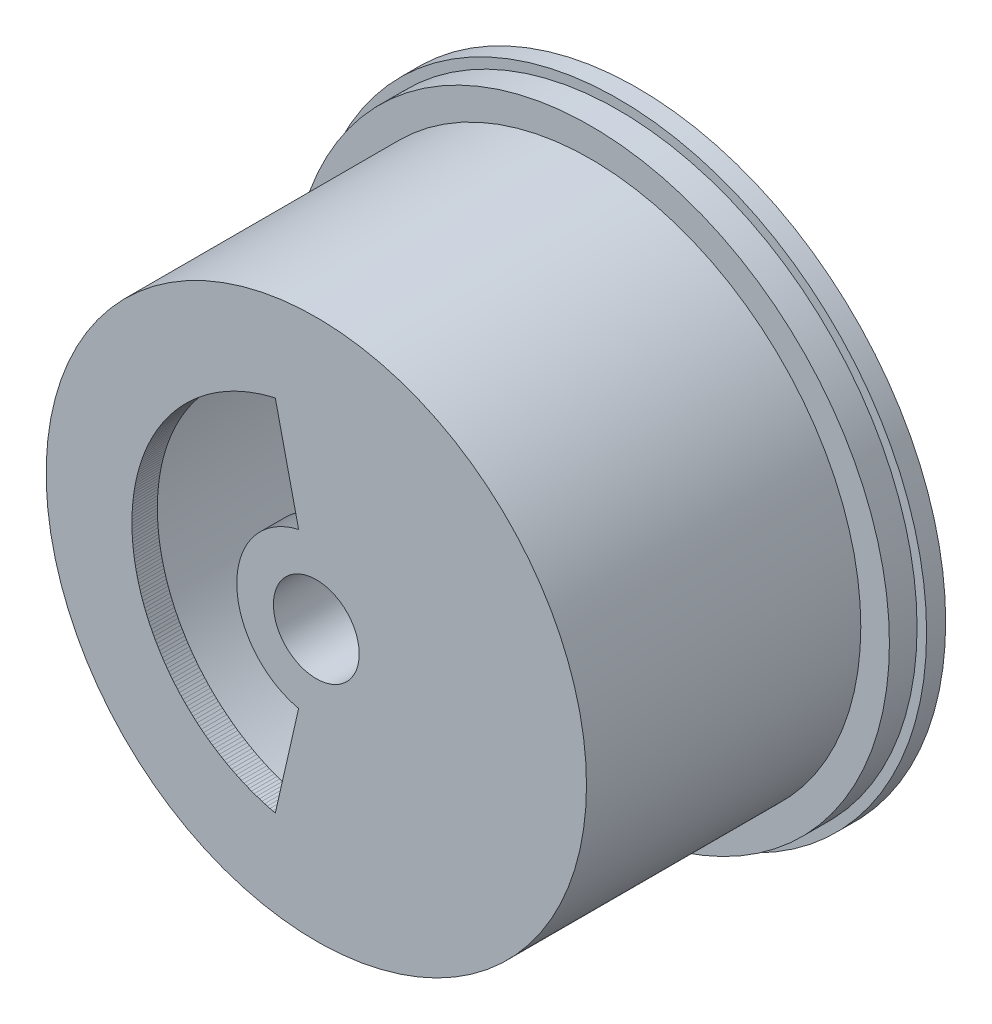
SolidWorks part; units mm, degrees
material "灰铸铁"
ref_plane "前视基准面" through (0, 0, 0) normal (0, 0, 1) x (1, 0, 0)
ref_plane "上视基准面" through (0, 0, 0) normal (0, 1, 0) x (1, 0, 0)
ref_plane "右视基准面" through (0, 0, 0) normal (1, 0, 0) x (0, 0, -1)
other "Configuration Table"
sketch "草图1" plane through (0, 0, 0) normal (0, 0, 1) x (1, 0, 0)
  circle A0 centre (0, 0) radius 97
extrude "01_FLANGE_D194" add sketch "草图1" along normal blind 6
ref_plane "Plane_Spigot" through (0, 0, 6) normal (0, 0, 1) x (1, 0, 0)
sketch "草图2" plane through (0, 0, 6) normal (0, 0, 1) x (1, 0, 0)
  circle A0 centre (0, 0) radius 94
extrude "02_SPIGOT_D188" add sketch "草图2" along normal blind 8.7
ref_plane "Plane_Body" through (0, 0, 14.7) normal (0, 0, 1) x (1, 0, 0)
sketch "草图3" plane through (0, 0, 14.7) normal (0, 0, 1) x (1, 0, 0)
  circle A0 centre (0, 0) radius 85
extrude "03_BODY_D170" add sketch "草图3" along normal blind 86.3
sketch "草图4" plane through (0, 0, 0) normal (0, 0, 1) x (1, 0, 0)
  circle A0 centre (0, 0) radius 79
extrude "04_BORE_D158" cut sketch "草图4" along normal blind 6
sketch "草图5" plane through (0, 0, 6) normal (0, 0, 1) x (1, 0, 0)
  circle A0 centre (0, 0) radius 75
extrude "05_BORE_D150" cut sketch "草图5" along normal blind 87
ref_plane "Plane_Boss42" through (0, 0, 88) normal (0, 0, 1) x (1, 0, 0)
sketch "草图6" plane through (0, 0, 88) normal (0, 0, 1) x (1, 0, 0)
  circle A0 centre (0, 0) radius 21
extrude "06_BOSS_D42" add sketch "草图6" along normal blind 5
ref_plane "Plane_Boss30" through (0, 0, 81) normal (0, 0, 1) x (1, 0, 0)
sketch "草图7" plane through (0, 0, 81) normal (0, 0, 1) x (1, 0, 0)
  circle A0 centre (0, 0) radius 15
extrude "07_BOSS_D30" add sketch "草图7" along normal blind 7
ref_plane "基准面5" through (0, 0, 81) normal (0, 0, 1) x (1, 0, 0)
sketch "草图8" plane through (0, 0, 81) normal (0, 0, 1) x (1, 0, 0)
  circle A0 centre (0, 0) radius 13.5
extrude "08_BORE_D27" cut sketch "草图8" along normal blind 20
ref_plane "Plane_EndWall" through (0, 0, 93) normal (0, 0, 1) x (1, 0, 0)
sketch "草图9" plane through (0, 0, 93) normal (0, 0, 1) x (1, 0, 0)
  line L0 (-12.8992, 56.5474) -> (-13.7437, 56.3481)
  line L1 (-13.7437, 56.3481) -> (-14.5852, 56.1362)
  line L2 (-14.5852, 56.1362) -> (-15.4234, 55.9117)
  line L3 (-15.4234, 55.9117) -> (-16.2582, 55.6747)
  line L4 (-16.2582, 55.6747) -> (-17.0893, 55.4252)
  line L5 (-17.0893, 55.4252) -> (-17.9166, 55.1634)
  line L6 (-17.9166, 55.1634) -> (-18.7398, 54.8891)
  line L7 (-18.7398, 54.8891) -> (-19.5589, 54.6026)
  line L8 (-19.5589, 54.6026) -> (-20.3736, 54.3039)
  line L9 (-20.3736, 54.3039) -> (-21.1838, 53.993)
  line L10 (-21.1838, 53.993) -> (-21.9892, 53.6701)
  line L11 (-21.9892, 53.6701) -> (-22.7897, 53.3351)
  line L12 (-22.7897, 53.3351) -> (-23.5851, 52.9882)
  line L13 (-23.5851, 52.9882) -> (-24.3752, 52.6294)
  line L14 (-24.3752, 52.6294) -> (-25.1598, 52.2588)
  line L15 (-25.1598, 52.2588) -> (-25.9388, 51.8765)
  line L16 (-25.9388, 51.8765) -> (-26.7121, 51.4827)
  line L17 (-26.7121, 51.4827) -> (-27.4793, 51.0773)
  line L18 (-27.4793, 51.0773) -> (-28.2404, 50.6605)
  line L19 (-28.2404, 50.6605) -> (-28.9951, 50.2323)
  line L20 (-28.9951, 50.2323) -> (-29.7434, 49.7929)
  line L21 (-29.7434, 49.7929) -> (-30.485, 49.3423)
  line L22 (-30.485, 49.3423) -> (-31.2198, 48.8807)
  line L23 (-31.2198, 48.8807) -> (-31.9476, 48.4082)
  line L24 (-31.9476, 48.4082) -> (-32.6682, 47.9248)
  line L25 (-32.6682, 47.9248) -> (-33.3816, 47.4307)
  line L26 (-33.3816, 47.4307) -> (-34.0874, 46.926)
  line L27 (-34.0874, 46.926) -> (-34.7857, 46.4107)
  line L28 (-34.7857, 46.4107) -> (-35.4761, 45.8851)
  line L29 (-35.4761, 45.8851) -> (-36.1586, 45.3492)
  line L30 (-36.1586, 45.3492) -> (-36.8331, 44.8032)
  line L31 (-36.8331, 44.8032) -> (-37.4992, 44.2471)
  line L32 (-37.4992, 44.2471) -> (-38.157, 43.6812)
  line L33 (-38.157, 43.6812) -> (-38.8062, 43.1054)
  line L34 (-38.8062, 43.1054) -> (-39.4468, 42.52)
  line L35 (-39.4468, 42.52) -> (-40.0785, 41.9251)
  line L36 (-40.0785, 41.9251) -> (-40.7012, 41.3208)
  line L37 (-40.7012, 41.3208) -> (-41.3149, 40.7073)
  line L38 (-41.3149, 40.7073) -> (-41.9193, 40.0846)
  line L39 (-41.9193, 40.0846) -> (-42.5143, 39.453)
  line L40 (-42.5143, 39.453) -> (-43.0998, 38.8125)
  line L41 (-43.0998, 38.8125) -> (-43.6756, 38.1634)
  line L42 (-43.6756, 38.1634) -> (-44.2417, 37.5057)
  line L43 (-44.2417, 37.5057) -> (-44.7978, 36.8396)
  line L44 (-44.7978, 36.8396) -> (-45.344, 36.1652)
  line L45 (-45.344, 36.1652) -> (-45.88, 35.4828)
  line L46 (-45.88, 35.4828) -> (-46.4057, 34.7924)
  line L47 (-46.4057, 34.7924) -> (-46.921, 34.0943)
  line L48 (-46.921, 34.0943) -> (-47.4258, 33.3885)
  line L49 (-47.4258, 33.3885) -> (-47.92, 32.6752)
  line L50 (-47.92, 32.6752) -> (-48.4035, 31.9546)
  line L51 (-48.4035, 31.9546) -> (-48.8762, 31.2269)
  line L52 (-48.8762, 31.2269) -> (-49.3379, 30.4922)
  line L53 (-49.3379, 30.4922) -> (-49.7885, 29.7506)
  line L54 (-49.7885, 29.7506) -> (-50.2281, 29.0024)
  line L55 (-50.2281, 29.0024) -> (-50.6563, 28.2477)
  line L56 (-50.6563, 28.2477) -> (-51.0733, 27.4867)
  line L57 (-51.0733, 27.4867) -> (-51.4788, 26.7195)
  line L58 (-51.4788, 26.7195) -> (-51.8728, 25.9464)
  line L59 (-51.8728, 25.9464) -> (-52.2551, 25.1674)
  line L60 (-52.2551, 25.1674) -> (-52.6258, 24.3828)
  line L61 (-52.6258, 24.3828) -> (-52.9847, 23.5928)
  line L62 (-52.9847, 23.5928) -> (-53.3318, 22.7974)
  line L63 (-53.3318, 22.7974) -> (-53.6669, 21.997)
  line L64 (-53.6669, 21.997) -> (-53.9899, 21.1916)
  line L65 (-53.9899, 21.1916) -> (-54.3009, 20.3815)
  line L66 (-54.3009, 20.3815) -> (-54.5998, 19.5669)
  line L67 (-54.5998, 19.5669) -> (-54.8864, 18.7478)
  line L68 (-54.8864, 18.7478) -> (-55.1608, 17.9246)
  line L69 (-55.1608, 17.9246) -> (-55.4227, 17.0973)
  line L70 (-55.4227, 17.0973) -> (-55.6723, 16.2663)
  line L71 (-55.6723, 16.2663) -> (-55.9095, 15.4315)
  line L72 (-55.9095, 15.4315) -> (-56.1341, 14.5934)
  line L73 (-56.1341, 14.5934) -> (-56.3461, 13.7519)
  line L74 (-56.3461, 13.7519) -> (-56.5456, 12.9074)
  line L75 (-56.5456, 12.9074) -> (-56.7323, 12.06)
  line L76 (-56.7323, 12.06) -> (-56.9064, 11.2099)
  line L77 (-56.9064, 11.2099) -> (-57.0677, 10.3572)
  line L78 (-57.0677, 10.3572) -> (-57.2163, 9.5023)
  line L79 (-57.2163, 9.5023) -> (-57.3521, 8.6452)
  line L80 (-57.3521, 8.6452) -> (-57.475, 7.7862)
  line L81 (-57.475, 7.7862) -> (-57.585, 6.9255)
  line L82 (-57.585, 6.9255) -> (-57.6822, 6.0632)
  line L83 (-57.6822, 6.0632) -> (-57.7665, 5.1996)
  line L84 (-57.7665, 5.1996) -> (-57.8378, 4.3347)
  line L85 (-57.8378, 4.3347) -> (-57.8962, 3.469)
  line L86 (-57.8962, 3.469) -> (-57.9416, 2.6024)
  line L87 (-57.9416, 2.6024) -> (-57.974, 1.7353)
  line L88 (-57.974, 1.7353) -> (-57.9935, 0.8677)
  line L89 (-57.9935, 0.8677) -> (-58, 0)
  line L90 (-58, 0) -> (-57.9935, -0.8677)
  line L91 (-57.9935, -0.8677) -> (-57.974, -1.7353)
  line L92 (-57.974, -1.7353) -> (-57.9416, -2.6024)
  line L93 (-57.9416, -2.6024) -> (-57.8962, -3.469)
  line L94 (-57.8962, -3.469) -> (-57.8378, -4.3347)
  line L95 (-57.8378, -4.3347) -> (-57.7665, -5.1996)
  line L96 (-57.7665, -5.1996) -> (-57.6822, -6.0632)
  line L97 (-57.6822, -6.0632) -> (-57.585, -6.9255)
  line L98 (-57.585, -6.9255) -> (-57.475, -7.7862)
  line L99 (-57.475, -7.7862) -> (-57.3521, -8.6452)
  line L100 (-57.3521, -8.6452) -> (-57.2163, -9.5023)
  line L101 (-57.2163, -9.5023) -> (-57.0677, -10.3572)
  line L102 (-57.0677, -10.3572) -> (-56.9064, -11.2099)
  line L103 (-56.9064, -11.2099) -> (-56.7323, -12.06)
  line L104 (-56.7323, -12.06) -> (-56.5456, -12.9074)
  line L105 (-56.5456, -12.9074) -> (-56.3461, -13.7519)
  line L106 (-56.3461, -13.7519) -> (-56.1341, -14.5934)
  line L107 (-56.1341, -14.5934) -> (-55.9095, -15.4315)
  line L108 (-55.9095, -15.4315) -> (-55.6723, -16.2663)
  line L109 (-55.6723, -16.2663) -> (-55.4227, -17.0973)
  line L110 (-55.4227, -17.0973) -> (-55.1608, -17.9246)
  line L111 (-55.1608, -17.9246) -> (-54.8864, -18.7478)
  line L112 (-54.8864, -18.7478) -> (-54.5998, -19.5669)
  line L113 (-54.5998, -19.5669) -> (-54.3009, -20.3815)
  line L114 (-54.3009, -20.3815) -> (-53.9899, -21.1916)
  line L115 (-53.9899, -21.1916) -> (-53.6669, -21.997)
  line L116 (-53.6669, -21.997) -> (-53.3318, -22.7974)
  line L117 (-53.3318, -22.7974) -> (-52.9847, -23.5928)
  line L118 (-52.9847, -23.5928) -> (-52.6258, -24.3828)
  line L119 (-52.6258, -24.3828) -> (-52.2551, -25.1674)
  line L120 (-52.2551, -25.1674) -> (-51.8728, -25.9464)
  line L121 (-51.8728, -25.9464) -> (-51.4788, -26.7195)
  line L122 (-51.4788, -26.7195) -> (-51.0733, -27.4867)
  line L123 (-51.0733, -27.4867) -> (-50.6563, -28.2477)
  line L124 (-50.6563, -28.2477) -> (-50.2281, -29.0024)
  line L125 (-50.2281, -29.0024) -> (-49.7885, -29.7506)
  line L126 (-49.7885, -29.7506) -> (-49.3379, -30.4922)
  line L127 (-49.3379, -30.4922) -> (-48.8762, -31.2269)
  line L128 (-48.8762, -31.2269) -> (-48.4035, -31.9546)
  line L129 (-48.4035, -31.9546) -> (-47.92, -32.6752)
  line L130 (-47.92, -32.6752) -> (-47.4258, -33.3885)
  line L131 (-47.4258, -33.3885) -> (-46.921, -34.0943)
  line L132 (-46.921, -34.0943) -> (-46.4057, -34.7924)
  line L133 (-46.4057, -34.7924) -> (-45.88, -35.4828)
  line L134 (-45.88, -35.4828) -> (-45.344, -36.1652)
  line L135 (-45.344, -36.1652) -> (-44.7978, -36.8396)
  line L136 (-44.7978, -36.8396) -> (-44.2417, -37.5057)
  line L137 (-44.2417, -37.5057) -> (-43.6756, -38.1634)
  line L138 (-43.6756, -38.1634) -> (-43.0998, -38.8125)
  line L139 (-43.0998, -38.8125) -> (-42.5143, -39.453)
  line L140 (-42.5143, -39.453) -> (-41.9193, -40.0846)
  line L141 (-41.9193, -40.0846) -> (-41.3149, -40.7073)
  line L142 (-41.3149, -40.7073) -> (-40.7012, -41.3208)
  line L143 (-40.7012, -41.3208) -> (-40.0785, -41.9251)
  line L144 (-40.0785, -41.9251) -> (-39.4468, -42.52)
  line L145 (-39.4468, -42.52) -> (-38.8062, -43.1054)
  line L146 (-38.8062, -43.1054) -> (-38.157, -43.6812)
  line L147 (-38.157, -43.6812) -> (-37.4992, -44.2471)
  line L148 (-37.4992, -44.2471) -> (-36.8331, -44.8032)
  line L149 (-36.8331, -44.8032) -> (-36.1586, -45.3492)
  line L150 (-36.1586, -45.3492) -> (-35.4761, -45.8851)
  line L151 (-35.4761, -45.8851) -> (-34.7857, -46.4107)
  line L152 (-34.7857, -46.4107) -> (-34.0874, -46.926)
  line L153 (-34.0874, -46.926) -> (-33.3816, -47.4307)
  line L154 (-33.3816, -47.4307) -> (-32.6682, -47.9248)
  line L155 (-32.6682, -47.9248) -> (-31.9476, -48.4082)
  line L156 (-31.9476, -48.4082) -> (-31.2198, -48.8807)
  line L157 (-31.2198, -48.8807) -> (-30.485, -49.3423)
  line L158 (-30.485, -49.3423) -> (-29.7434, -49.7929)
  line L159 (-29.7434, -49.7929) -> (-28.9951, -50.2323)
  line L160 (-28.9951, -50.2323) -> (-28.2404, -50.6605)
  line L161 (-28.2404, -50.6605) -> (-27.4793, -51.0773)
  line L162 (-27.4793, -51.0773) -> (-26.7121, -51.4827)
  line L163 (-26.7121, -51.4827) -> (-25.9388, -51.8765)
  line L164 (-25.9388, -51.8765) -> (-25.1598, -52.2588)
  line L165 (-25.1598, -52.2588) -> (-24.3752, -52.6294)
  line L166 (-24.3752, -52.6294) -> (-23.5851, -52.9882)
  line L167 (-23.5851, -52.9882) -> (-22.7897, -53.3351)
  line L168 (-22.7897, -53.3351) -> (-21.9892, -53.6701)
  line L169 (-21.9892, -53.6701) -> (-21.1838, -53.993)
  line L170 (-21.1838, -53.993) -> (-20.3736, -54.3039)
  line L171 (-20.3736, -54.3039) -> (-19.5589, -54.6026)
  line L172 (-19.5589, -54.6026) -> (-18.7398, -54.8891)
  line L173 (-18.7398, -54.8891) -> (-17.9166, -55.1634)
  line L174 (-17.9166, -55.1634) -> (-17.0893, -55.4252)
  line L175 (-17.0893, -55.4252) -> (-16.2582, -55.6747)
  line L176 (-16.2582, -55.6747) -> (-15.4234, -55.9117)
  line L177 (-15.4234, -55.9117) -> (-14.5852, -56.1362)
  line L178 (-14.5852, -56.1362) -> (-13.7437, -56.3481)
  line L179 (-13.7437, -56.3481) -> (-12.8992, -56.5474)
  line L180 (-12.8992, -56.5474) -> (-5.56, -24.3739)
  line L181 (-5.56, -24.3739) -> (-5.924, -24.288)
  line L182 (-5.924, -24.288) -> (-6.2867, -24.1966)
  line L183 (-6.2867, -24.1966) -> (-6.648, -24.0999)
  line L184 (-6.648, -24.0999) -> (-7.0078, -23.9977)
  line L185 (-7.0078, -23.9977) -> (-7.3661, -23.8902)
  line L186 (-7.3661, -23.8902) -> (-7.7227, -23.7773)
  line L187 (-7.7227, -23.7773) -> (-8.0775, -23.6591)
  line L188 (-8.0775, -23.6591) -> (-8.4306, -23.5356)
  line L189 (-8.4306, -23.5356) -> (-8.7817, -23.4069)
  line L190 (-8.7817, -23.4069) -> (-9.1309, -23.2729)
  line L191 (-9.1309, -23.2729) -> (-9.4781, -23.1336)
  line L192 (-9.4781, -23.1336) -> (-9.8231, -22.9893)
  line L193 (-9.8231, -22.9893) -> (-10.166, -22.8397)
  line L194 (-10.166, -22.8397) -> (-10.5065, -22.6851)
  line L195 (-10.5065, -22.6851) -> (-10.8448, -22.5253)
  line L196 (-10.8448, -22.5253) -> (-11.1805, -22.3606)
  line L197 (-11.1805, -22.3606) -> (-11.5138, -22.1908)
  line L198 (-11.5138, -22.1908) -> (-11.8445, -22.0161)
  line L199 (-11.8445, -22.0161) -> (-12.1726, -21.8364)
  line L200 (-12.1726, -21.8364) -> (-12.4979, -21.6518)
  line L201 (-12.4979, -21.6518) -> (-12.8204, -21.4624)
  line L202 (-12.8204, -21.4624) -> (-13.1401, -21.2682)
  line L203 (-13.1401, -21.2682) -> (-13.4568, -21.0693)
  line L204 (-13.4568, -21.0693) -> (-13.7705, -20.8656)
  line L205 (-13.7705, -20.8656) -> (-14.0811, -20.6572)
  line L206 (-14.0811, -20.6572) -> (-14.3886, -20.4443)
  line L207 (-14.3886, -20.4443) -> (-14.6929, -20.2267)
  line L208 (-14.6929, -20.2267) -> (-14.9938, -20.0046)
  line L209 (-14.9938, -20.0046) -> (-15.2914, -19.7781)
  line L210 (-15.2914, -19.7781) -> (-15.5856, -19.5471)
  line L211 (-15.5856, -19.5471) -> (-15.8763, -19.3117)
  line L212 (-15.8763, -19.3117) -> (-16.1635, -19.072)
  line L213 (-16.1635, -19.072) -> (-16.447, -18.8281)
  line L214 (-16.447, -18.8281) -> (-16.7268, -18.5799)
  line L215 (-16.7268, -18.5799) -> (-17.0029, -18.3276)
  line L216 (-17.0029, -18.3276) -> (-17.2752, -18.0712)
  line L217 (-17.2752, -18.0712) -> (-17.5436, -17.8107)
  line L218 (-17.5436, -17.8107) -> (-17.8081, -17.5462)
  line L219 (-17.8081, -17.5462) -> (-18.0687, -17.2778)
  line L220 (-18.0687, -17.2778) -> (-18.3251, -17.0056)
  line L221 (-18.3251, -17.0056) -> (-18.5775, -16.7295)
  line L222 (-18.5775, -16.7295) -> (-18.8257, -16.4497)
  line L223 (-18.8257, -16.4497) -> (-19.0697, -16.1662)
  line L224 (-19.0697, -16.1662) -> (-19.3094, -15.8791)
  line L225 (-19.3094, -15.8791) -> (-19.5448, -15.5885)
  line L226 (-19.5448, -15.5885) -> (-19.7758, -15.2943)
  line L227 (-19.7758, -15.2943) -> (-20.0024, -14.9967)
  line L228 (-20.0024, -14.9967) -> (-20.2246, -14.6958)
  line L229 (-20.2246, -14.6958) -> (-20.4422, -14.3916)
  line L230 (-20.4422, -14.3916) -> (-20.6552, -14.0841)
  line L231 (-20.6552, -14.0841) -> (-20.8636, -13.7736)
  line L232 (-20.8636, -13.7736) -> (-21.0673, -13.4599)
  line L233 (-21.0673, -13.4599) -> (-21.2663, -13.1432)
  line L234 (-21.2663, -13.1432) -> (-21.4606, -12.8236)
  line L235 (-21.4606, -12.8236) -> (-21.65, -12.501)
  line L236 (-21.65, -12.501) -> (-21.8346, -12.1757)
  line L237 (-21.8346, -12.1757) -> (-22.0143, -11.8477)
  line L238 (-22.0143, -11.8477) -> (-22.1891, -11.517)
  line L239 (-22.1891, -11.517) -> (-22.359, -11.1838)
  line L240 (-22.359, -11.1838) -> (-22.5238, -10.848)
  line L241 (-22.5238, -10.848) -> (-22.6835, -10.5098)
  line L242 (-22.6835, -10.5098) -> (-22.8382, -10.1693)
  line L243 (-22.8382, -10.1693) -> (-22.9878, -9.8265)
  line L244 (-22.9878, -9.8265) -> (-23.1323, -9.4815)
  line L245 (-23.1323, -9.4815) -> (-23.2715, -9.1343)
  line L246 (-23.2715, -9.1343) -> (-23.4056, -8.7851)
  line L247 (-23.4056, -8.7851) -> (-23.5344, -8.434)
  line L248 (-23.5344, -8.434) -> (-23.6579, -8.081)
  line L249 (-23.6579, -8.081) -> (-23.7762, -7.7261)
  line L250 (-23.7762, -7.7261) -> (-23.8891, -7.3695)
  line L251 (-23.8891, -7.3695) -> (-23.9967, -7.0113)
  line L252 (-23.9967, -7.0113) -> (-24.0989, -6.6515)
  line L253 (-24.0989, -6.6515) -> (-24.1957, -6.2902)
  line L254 (-24.1957, -6.2902) -> (-24.2871, -5.9275)
  line L255 (-24.2871, -5.9275) -> (-24.3731, -5.5635)
  line L256 (-24.3731, -5.5635) -> (-24.4536, -5.1983)
  line L257 (-24.4536, -5.1983) -> (-24.5286, -4.8318)
  line L258 (-24.5286, -4.8318) -> (-24.5982, -4.4643)
  line L259 (-24.5982, -4.4643) -> (-24.6622, -4.0958)
  line L260 (-24.6622, -4.0958) -> (-24.7207, -3.7264)
  line L261 (-24.7207, -3.7264) -> (-24.7737, -3.3561)
  line L262 (-24.7737, -3.3561) -> (-24.8211, -2.9851)
  line L263 (-24.8211, -2.9851) -> (-24.863, -2.6135)
  line L264 (-24.863, -2.6135) -> (-24.8993, -2.2412)
  line L265 (-24.8993, -2.2412) -> (-24.9301, -1.8684)
  line L266 (-24.9301, -1.8684) -> (-24.9552, -1.4952)
  line L267 (-24.9552, -1.4952) -> (-24.9748, -1.1217)
  line L268 (-24.9748, -1.1217) -> (-24.9888, -0.748)
  line L269 (-24.9888, -0.748) -> (-24.9972, -0.374)
  line L270 (-24.9972, -0.374) -> (-25, 0)
  line L271 (-25, 0) -> (-24.9972, 0.374)
  line L272 (-24.9972, 0.374) -> (-24.9888, 0.748)
  line L273 (-24.9888, 0.748) -> (-24.9748, 1.1217)
  line L274 (-24.9748, 1.1217) -> (-24.9552, 1.4952)
  line L275 (-24.9552, 1.4952) -> (-24.9301, 1.8684)
  line L276 (-24.9301, 1.8684) -> (-24.8993, 2.2412)
  line L277 (-24.8993, 2.2412) -> (-24.863, 2.6135)
  line L278 (-24.863, 2.6135) -> (-24.8211, 2.9851)
  line L279 (-24.8211, 2.9851) -> (-24.7737, 3.3561)
  line L280 (-24.7737, 3.3561) -> (-24.7207, 3.7264)
  line L281 (-24.7207, 3.7264) -> (-24.6622, 4.0958)
  line L282 (-24.6622, 4.0958) -> (-24.5982, 4.4643)
  line L283 (-24.5982, 4.4643) -> (-24.5286, 4.8318)
  line L284 (-24.5286, 4.8318) -> (-24.4536, 5.1983)
  line L285 (-24.4536, 5.1983) -> (-24.3731, 5.5635)
  line L286 (-24.3731, 5.5635) -> (-24.2871, 5.9275)
  line L287 (-24.2871, 5.9275) -> (-24.1957, 6.2902)
  line L288 (-24.1957, 6.2902) -> (-24.0989, 6.6515)
  line L289 (-24.0989, 6.6515) -> (-23.9967, 7.0113)
  line L290 (-23.9967, 7.0113) -> (-23.8891, 7.3695)
  line L291 (-23.8891, 7.3695) -> (-23.7762, 7.7261)
  line L292 (-23.7762, 7.7261) -> (-23.6579, 8.081)
  line L293 (-23.6579, 8.081) -> (-23.5344, 8.434)
  line L294 (-23.5344, 8.434) -> (-23.4056, 8.7851)
  line L295 (-23.4056, 8.7851) -> (-23.2715, 9.1343)
  line L296 (-23.2715, 9.1343) -> (-23.1323, 9.4815)
  line L297 (-23.1323, 9.4815) -> (-22.9878, 9.8265)
  line L298 (-22.9878, 9.8265) -> (-22.8382, 10.1693)
  line L299 (-22.8382, 10.1693) -> (-22.6835, 10.5098)
  line L300 (-22.6835, 10.5098) -> (-22.5238, 10.848)
  line L301 (-22.5238, 10.848) -> (-22.359, 11.1838)
  line L302 (-22.359, 11.1838) -> (-22.1891, 11.517)
  line L303 (-22.1891, 11.517) -> (-22.0143, 11.8477)
  line L304 (-22.0143, 11.8477) -> (-21.8346, 12.1757)
  line L305 (-21.8346, 12.1757) -> (-21.65, 12.501)
  line L306 (-21.65, 12.501) -> (-21.4606, 12.8236)
  line L307 (-21.4606, 12.8236) -> (-21.2663, 13.1432)
  line L308 (-21.2663, 13.1432) -> (-21.0673, 13.4599)
  line L309 (-21.0673, 13.4599) -> (-20.8636, 13.7736)
  line L310 (-20.8636, 13.7736) -> (-20.6552, 14.0841)
  line L311 (-20.6552, 14.0841) -> (-20.4422, 14.3916)
  line L312 (-20.4422, 14.3916) -> (-20.2246, 14.6958)
  line L313 (-20.2246, 14.6958) -> (-20.0024, 14.9967)
  line L314 (-20.0024, 14.9967) -> (-19.7758, 15.2943)
  line L315 (-19.7758, 15.2943) -> (-19.5448, 15.5885)
  line L316 (-19.5448, 15.5885) -> (-19.3094, 15.8791)
  line L317 (-19.3094, 15.8791) -> (-19.0697, 16.1662)
  line L318 (-19.0697, 16.1662) -> (-18.8257, 16.4497)
  line L319 (-18.8257, 16.4497) -> (-18.5775, 16.7295)
  line L320 (-18.5775, 16.7295) -> (-18.3251, 17.0056)
  line L321 (-18.3251, 17.0056) -> (-18.0687, 17.2778)
  line L322 (-18.0687, 17.2778) -> (-17.8081, 17.5462)
  line L323 (-17.8081, 17.5462) -> (-17.5436, 17.8107)
  line L324 (-17.5436, 17.8107) -> (-17.2752, 18.0712)
  line L325 (-17.2752, 18.0712) -> (-17.0029, 18.3276)
  line L326 (-17.0029, 18.3276) -> (-16.7268, 18.5799)
  line L327 (-16.7268, 18.5799) -> (-16.447, 18.8281)
  line L328 (-16.447, 18.8281) -> (-16.1635, 19.072)
  line L329 (-16.1635, 19.072) -> (-15.8763, 19.3117)
  line L330 (-15.8763, 19.3117) -> (-15.5856, 19.5471)
  line L331 (-15.5856, 19.5471) -> (-15.2914, 19.7781)
  line L332 (-15.2914, 19.7781) -> (-14.9938, 20.0046)
  line L333 (-14.9938, 20.0046) -> (-14.6929, 20.2267)
  line L334 (-14.6929, 20.2267) -> (-14.3886, 20.4443)
  line L335 (-14.3886, 20.4443) -> (-14.0811, 20.6572)
  line L336 (-14.0811, 20.6572) -> (-13.7705, 20.8656)
  line L337 (-13.7705, 20.8656) -> (-13.4568, 21.0693)
  line L338 (-13.4568, 21.0693) -> (-13.1401, 21.2682)
  line L339 (-13.1401, 21.2682) -> (-12.8204, 21.4624)
  line L340 (-12.8204, 21.4624) -> (-12.4979, 21.6518)
  line L341 (-12.4979, 21.6518) -> (-12.1726, 21.8364)
  line L342 (-12.1726, 21.8364) -> (-11.8445, 22.0161)
  line L343 (-11.8445, 22.0161) -> (-11.5138, 22.1908)
  line L344 (-11.5138, 22.1908) -> (-11.1805, 22.3606)
  line L345 (-11.1805, 22.3606) -> (-10.8448, 22.5253)
  line L346 (-10.8448, 22.5253) -> (-10.5065, 22.6851)
  line L347 (-10.5065, 22.6851) -> (-10.166, 22.8397)
  line L348 (-10.166, 22.8397) -> (-9.8231, 22.9893)
  line L349 (-9.8231, 22.9893) -> (-9.4781, 23.1336)
  line L350 (-9.4781, 23.1336) -> (-9.1309, 23.2729)
  line L351 (-9.1309, 23.2729) -> (-8.7817, 23.4069)
  line L352 (-8.7817, 23.4069) -> (-8.4306, 23.5356)
  line L353 (-8.4306, 23.5356) -> (-8.0775, 23.6591)
  line L354 (-8.0775, 23.6591) -> (-7.7227, 23.7773)
  line L355 (-7.7227, 23.7773) -> (-7.3661, 23.8902)
  line L356 (-7.3661, 23.8902) -> (-7.0078, 23.9977)
  line L357 (-7.0078, 23.9977) -> (-6.648, 24.0999)
  line L358 (-6.648, 24.0999) -> (-6.2867, 24.1966)
  line L359 (-6.2867, 24.1966) -> (-5.924, 24.288)
  line L360 (-5.924, 24.288) -> (-5.56, 24.3739)
  line L361 (-5.56, 24.3739) -> (-12.8992, 56.5474)
extrude "09_FAN_WINDOW" cut sketch "草图9" along normal blind 8
sketch "草图10" plane through (0, 0, 0) normal (0, 0, 1) x (1, 0, 0)
  circle A0 centre (90.2215, 11.8779) radius 2.1
  circle A1 centre (84.073, 34.8242) radius 2.1
  circle A2 centre (72.1952, 55.3973) radius 2.1
  circle A3 centre (55.3973, 72.1952) radius 2.1
  circle A4 centre (34.8242, 84.073) radius 2.1
  circle A5 centre (11.8779, 90.2215) radius 2.1
  circle A6 centre (-11.8779, 90.2215) radius 2.1
  circle A7 centre (-34.8242, 84.073) radius 2.1
  circle A8 centre (-55.3973, 72.1952) radius 2.1
  circle A9 centre (-72.1952, 55.3973) radius 2.1
  circle A10 centre (-84.073, 34.8242) radius 2.1
  circle A11 centre (-90.2215, 11.8779) radius 2.1
  circle A12 centre (-90.2215, -11.8779) radius 2.1
  circle A13 centre (-84.073, -34.8242) radius 2.1
  circle A14 centre (-72.1952, -55.3973) radius 2.1
  circle A15 centre (-55.3973, -72.1952) radius 2.1
  circle A16 centre (-34.8242, -84.073) radius 2.1
  circle A17 centre (-11.8779, -90.2215) radius 2.1
  circle A18 centre (11.8779, -90.2215) radius 2.1
  circle A19 centre (34.8242, -84.073) radius 2.1
  circle A20 centre (55.3973, -72.1952) radius 2.1
  circle A21 centre (72.1952, -55.3973) radius 2.1
  circle A22 centre (84.073, -34.8242) radius 2.1
  circle A23 centre (90.2215, -11.8779) radius 2.1
extrude "10_HOLES_24_M5" cut sketch "草图10" along normal blind 6
